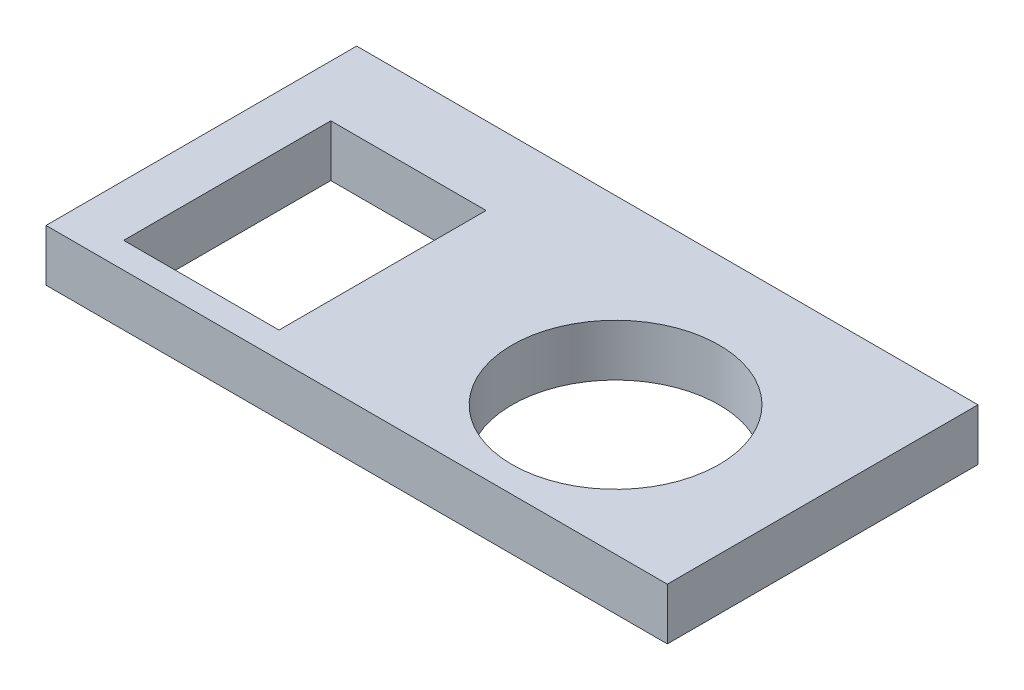
SolidWorks part; units mm, degrees
material "Kiefer"
ref_plane "Ebene vorne" through (0, 0, 0) normal (0, 0, 1) x (1, 0, 0)
ref_plane "Ebene oben" through (0, 0, 0) normal (0, 1, 0) x (1, 0, 0)
ref_plane "Ebene rechts" through (0, 0, 0) normal (1, 0, 0) x (0, 0, -1)
sketch "Skizze1" plane through (0, 0, 0) normal (0, 1, 0) x (1, 0, 0)
  line L1 (-60, 25) -> (60, 25)
  line L2 (-60, 25) -> (-60, -25)
  line L3 (-60, -25) -> (60, -25)
  line L4 (60, 25) -> (60, -25)
  line L5 (-60, 25) -> (60, -25) construction
  line L6 (-60, -25) -> (60, 25) construction
  point P0 (0, 0)
  dimension "D1" = 50
  dimension "D2" = 120
extrude "Aufsatz-Linear austragen1" add sketch "Skizze1" along normal blind 10
sketch "Skizze3" plane through (0, 10, 0) normal (0, 1, 0) x (1, 0, 0)
  line L0 (-60, -25) -> (60, -25) construction
  line L1 (60, 25) -> (-10, 25) construction
  line L2 (60, 25) -> (60, -25) construction
  line L3 (60, -25) -> (-10, -25) construction
  line L4 (-10, 25) -> (-10, -25) construction
  line L5 (60, 25) -> (-10, -25) construction
  line L6 (60, -25) -> (-10, 25) construction
  line L8 (-10, -25) -> (-60, -25) construction
  line L9 (-10, -25) -> (-10, 25) construction
  line L10 (-10, 25) -> (-60, 25) construction
  line L11 (-60, -25) -> (-60, 25) construction
  line L12 (-10, -25) -> (-60, 25) construction
  line L13 (-10, 25) -> (-60, -25) construction
  line L14 (-50, 20) -> (-20, 20)
  line L15 (-50, 20) -> (-50, -20)
  line L16 (-50, -20) -> (-20, -20)
  line L17 (-20, 20) -> (-20, -20)
  line L18 (-50, 20) -> (-20, -20) construction
  line L19 (-50, -20) -> (-20, 20) construction
  circle A0 centre (25, 0) radius 20
  point P4 (25, 0)
  point P12 (-35, 0)
  point P14 (-35, 0)
  dimension "D2" = 40
  dimension "D1" = 70
  dimension "D3" = 30
  dimension "D4" = 40
extrude "Schnitt-Linear austragen1" cut sketch "Skizze3" against normal through all
sketch "Skizze4" plane through (0, 10, 0) normal (0, 1, 0) x (1, 0, 0)
  line L0 (-60, 25) -> (-60, -25) construction
  line L1 (60, 25) -> (-60, 25)
  line L2 (60, 25) -> (60, 35)
  line L3 (60, 35) -> (-60, 35)
  line L4 (-60, 25) -> (-60, 35)
  line L5 (60, 25) -> (-60, 35) construction
  line L6 (60, 35) -> (-60, 25) construction
  point P4 (0, 30)
  dimension "D1" = 10
extrude "Aufsatz-Linear austragen2" add sketch "Skizze4" against normal up to surface (10 mm away) up to face at (-35, 0, 0)
